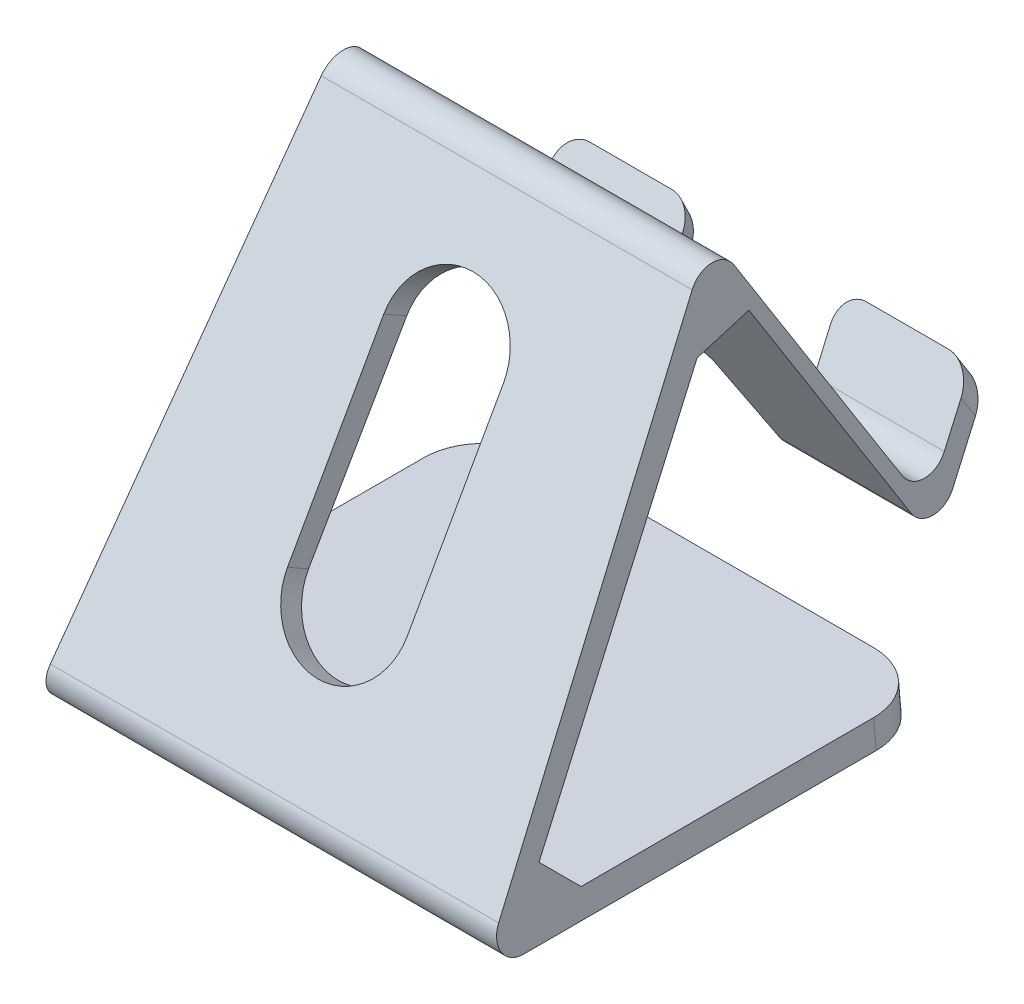
SolidWorks part; units mm, degrees
ref_plane "前视基准面" through (0, 0, 0) normal (0, 0, 1) x (1, 0, 0)
ref_plane "上视基准面" through (0, 0, 0) normal (0, 1, 0) x (1, 0, 0)
ref_plane "右视基准面" through (0, 0, 0) normal (1, 0, 0) x (0, 0, -1)
other "Configuration Table"
sketch "草图1" plane through (0, 0, 0) normal (1, 0, 0) x (0, 0, -1)
  line L0 (-69.3372, -13.9572) -> (5.6628, -13.9572)
  line L1 (5.6628, -13.9572) -> (5.6628, -9.4572)
  line L2 (5.6628, -9.4572) -> (-62.5411, -9.4572)
  line L3 (-62.5411, -9.4572) -> (-37.3069, 34.2498)
  line L7 (15.5409, 29.4201) -> (6.6628, 14.0428)
  line L8 (6.6628, 14.0428) -> (-24.3372, 66.0428)
  line L9 (-24.3372, 66.0428) -> (-69.3372, -13.9572)
  line L10 (-37.3069, 34.2498) -> (-22.7775, 59.4154)
  line L11 (-22.7775, 59.4154) -> (-6.5062, 32.1215)
  line L12 (-6.5062, 32.1215) -> (7.5394, 8.5612)
  line L13 (7.5394, 8.5612) -> (17.594, 25.9762)
  line L14 (15.5409, 29.4201) -> (17.594, 25.9762)
  point P2 (11.1018, 21.7315)
  point P13 (-49.924, 12.3963)
  dimension "D1" = 75
  dimension "D2" = 80
  dimension "D3" = 45
  dimension "D4" = 60
  dimension "D5" = 31
  dimension "D6" = 15.5
  dimension "D7" = 4.5
  dimension "D8" = 28
  dimension "D9" = 3.5
  dimension "D10" = 4
extrude "凸台-拉伸2" add sketch "草图1" along normal mid plane 75
sketch "草图3" plane through (0, 0, 0) normal (0, 0, 1) x (1, 0, 0)
  line L0 (-30, 66.0428) -> (-37.5, -13.9572)
  line L1 (37.5, 66.0428) -> (-37.5, 66.0428) construction
  line L2 (-37.5, 66.0428) -> (-37.5, -13.9572) construction
  line L3 (37.5, -13.9572) -> (-37.5, -13.9572) construction
  line L4 (0, 66.0428) -> (0, -13.9572) construction
  dimension "D1" = 30
extrude "切除-拉伸-薄壁7" cut sketch "草图3" against normal through all both and the other way through all thin
sketch "草图5" plane through (0, 0, 0) normal (0, 0, 1) x (1, 0, 0)
  line L0 (37.5, 66.0428) -> (37.5, -13.9572)
  line L1 (37.5, 66.0428) -> (-30, 66.0428) construction
  line L2 (30, 66.0428) -> (37.5, -13.9572)
  line L3 (30, 66.0428) -> (37.5, 66.0428)
extrude "切除-拉伸3" cut sketch "草图5" against normal through all both and the other way through all
sketch "草图6" plane through (0, 0, 0) normal (0, 0, 1) x (1, 0, 0)
  line L0 (0, -13.9572) -> (0, 66.0428) construction
  line L1 (37.5, -13.9572) -> (-37.5, -13.9572) construction
  line L2 (30, 66.0428) -> (-30, 66.0428) construction
sketch "草图7" plane through (0, 6.6127, -11.0923) normal (0, 0.5121, -0.8589) x (-1, 0, 0)
  line L0 (0, 69.1895) -> (0, -11.9885) construction
  line L1 (-30, 69.1895) -> (30, 69.1895) construction
  line L2 (-10, 28.6005) -> (10, 28.6005)
  line L3 (-10, 28.6005) -> (-15, 0)
  line L4 (-15, 0) -> (15, 0)
  line L5 (10, 28.6005) -> (15, 0)
  point P11 (0, 0)
  point P12 (0, 28.6005)
  dimension "D1" = 20
  dimension "D2" = 30
extrude "切除-拉伸4" cut sketch "草图7" against normal up to next and the other way through all
fillet "圆角1" radius 10 1 edges at (37.2891, -11.7072, -5.6628)
fillet "圆角2" radius 10 1 edges at (-37.2891, -11.7072, -5.6628)
chamfer "倒角1" distance 10 angle 45 2 edges at (0, 59.4154, 22.7775) (0, -9.4572, 62.5411)
fillet "圆角4" radius 4 1 edges at (0, -13.9572, 69.3372)
fillet "圆角5" radius 4 1 edges at (0, 66.0428, 24.3372)
fillet "圆角6" radius 4 2 edges at (24.1814, 14.0428, -6.6628) (-24.1814, 14.0428, -6.6628)
fillet "圆角7" radius 4 2 edges at (-24.8891, 8.5612, -7.5394) (24.8891, 8.5612, -7.5394)
fillet "圆角8" radius 4 4 edges at (-33.5948, 27.6982, -16.5674) (-12.3239, 27.6982, -16.5674) (12.3239, 27.6982, -16.5674) (33.5948, 27.6982, -16.5674)
sketch "草图8" plane through (0, 26.2731, 46.7077) normal (0, 0.4903, 0.8716) x (1, 0, 0)
  line L0 (0, 17.5153) -> (0, -14.8325) construction
  line L1 (0, -12.1648) -> (0, 57.5613) construction
  line L2 (9.8622, 17.5153) -> (9.8622, -14.8325)
  line L3 (-9.8622, 17.5153) -> (-9.8622, -14.8325)
  arc A0 (9.8622, 17.5153) -> (-9.8622, 17.5153) centre (0, 17.5153) ccw
  arc A1 (-9.8622, -14.8325) -> (9.8622, -14.8325) centre (0, -14.8325) ccw
  point P5 (0, 1.3414)
extrude "切除-拉伸5" cut sketch "草图8" against normal up to next
fillet "圆角9" radius 4 2 edges at (-10, 30.6531, 4.4352) (10, 30.6531, 4.4352)
sketch "草图9" plane through (0, 6.6127, -11.0923) normal (0, 0.5121, -0.8589) x (-1, 0, 0)
  line L0 (131.2204, 460.5966) -> (711.8871, 460.5966) construction
  line L1 (0, -11.9885) -> (0, 56.7273) construction
  spline S0 degree 3 poles (-6.606, 38.9534) (-6.8577, 39.9672) (-6.6625, 41.9581) (-5.7362, 44.3271) (-4.3352, 45.9317) (-2.4091, 47.1703) (-0.6638, 47.6835) (0.4689, 47.3852) knots 0 0 0 0 0.241647 0.464965 0.586301 0.737202 1 1 1 1
  spline S1 degree 3 poles (0.4689, 47.3852) (1.233, 47.9226) (2.4963, 49.236) (4.2416, 50.7222) (5.7571, 51.6118) (6.8908, 52.3494) (7.9799, 52.9111) (9.0093, 52.8979) (9.7726, 52.7018) (10.2686, 51.887) (10.1019, 50.6335) (9.7058, 48.9049) (8.6231, 46.0019) (7.4264, 43.8096) (6.3323, 42.4909) knots 0 0 0 0 0.125073 0.245843 0.307491 0.36129 0.429653 0.466683 0.499065 0.53048 0.584936 0.663141 0.77201 1 1 1 1
  spline S2 degree 3 poles (6.3323, 42.4909) (6.4213, 41.7448) (6.3442, 40.3605) (6.0006, 38.5796) (5.2527, 37.4432) (4.4757, 36.3459) (3.2071, 35.3579) (1.7055, 34.3485) (0.1631, 33.9241) (-0.7548, 34.0504) (-1.1303, 34.1193) knots 0 0 0 0 0.117073 0.219315 0.278544 0.329333 0.430146 0.528137 0.613566 0.67316 0.67316 0.67316 0.67316
  spline S3 degree 3 poles (-6.606, 38.9534) (-9.6943, 35.4194) (-16.0089, 21.2767) (-1.1303, 34.1193) knots 0 0 0 0 1 1 1 1
  spline S4 degree 3 poles (-5.9258, 36.8939) (-5.0293, 38.8483) (-2.1383, 42.5802) (1.9815, 45.2411) (4.6363, 45.3984) knots 0 0 0 0 0.452487 1 1 1 1
  spline S5 degree 3 poles (-2.7778, 34.475) (-2.9571, 34.5237) (-3.7784, 34.7746) (-5.0222, 35.4545) (-5.7302, 36.4108) (-5.9258, 36.8939) knots 0.76127 0.76127 0.76127 0.76127 0.790511 0.896348 0.975856 0.975856 0.975856 0.975856
  spline S6 degree 3 poles (-6.606, 38.9534) (-5.7113, 40.3112) (-3.8543, 43.5642) (-0.8584, 45.8265) (0.4689, 47.3852) knots 0 0 0 0 0.444343 1 1 1 1
  spline S7 degree 3 poles (-6.4122, 38.3719) (-7.1934, 36.9651) (-8.6896, 33.6791) (-10.6934, 28.0224) (-5.0554, 30.9863) knots 0 0 0 0 0.370525 1 1 1 1
  spline S8 degree 3 poles (-5.9258, 36.8939) (-6.3145, 36.4186) (-10.9017, 28.3823) (-2.6684, 33.7492) (-2.7778, 34.475) knots 0 0 0 0 0.48639 1 1 1 1
  spline S9 degree 3 poles (-6.4122, 38.3719) (-3.8819, 42.1275) (0.3667, 46.4294) (5.441, 50.8837) (8.319, 51.0983) (8.9434, 49.9473) (8.8658, 47.4695) (6.8678, 45.763) (5.7993, 44.623) knots 0 0 0 0 0.491979 0.675586 0.72728 0.775346 0.796473 1 1 1 1
  spline S10 degree 2 poles (4.6363, 45.3984) (4.9461, 45.0227) (5.2178, 44.623) knots 0 0 0 0.287155 0.287155 0.287155
  spline S11 degree 1 poles (5.7993, 44.623) (5.2178, 44.623) knots 0 0 1 1
  spline S12 degree 3 poles (-5.7046, 37.3543) (-4.9032, 35.8486) (-2.0678, 33.8266) (2.3604, 34.967) (4.576, 37.5062) (6.2204, 40.2219) (5.2504, 43.0523) (4.5133, 44.6551) (3.7712, 45.3) knots 0 0 0 0 0.248218 0.43884 0.599874 0.733439 0.868621 1 1 1 1
extrude "切除-拉伸19" cut sketch "草图9" against normal blind 0.5
